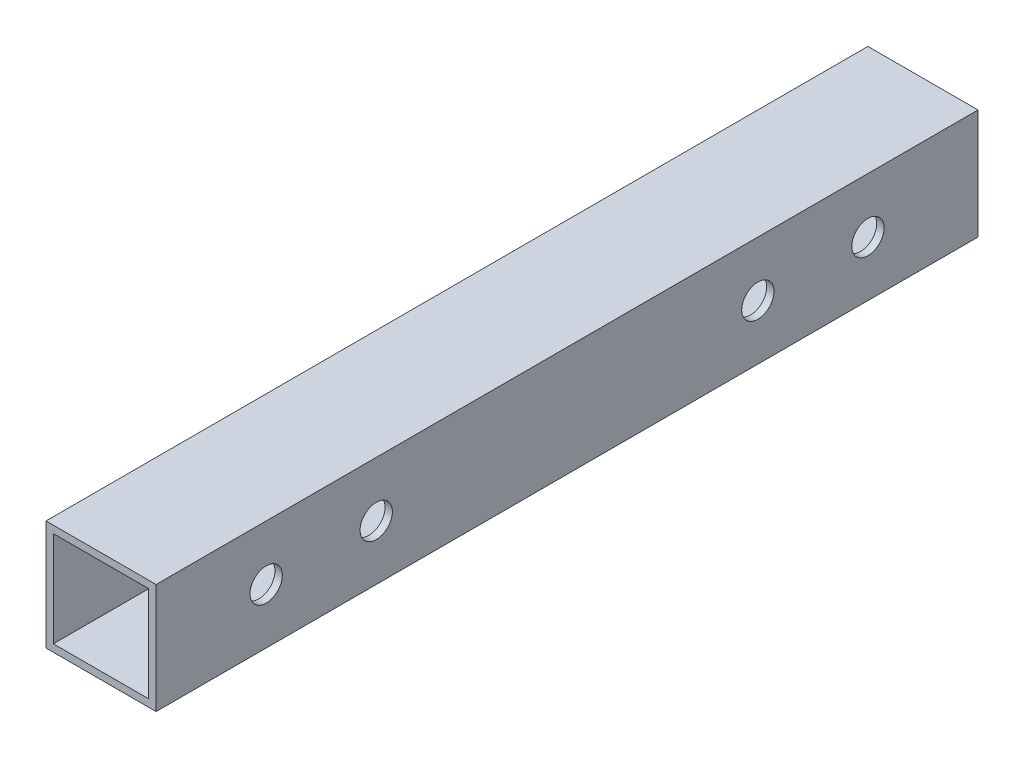
SolidWorks part; units mm, degrees
ref_plane "前视基准面" through (0, 0, 0) normal (0, 0, 1) x (1, 0, 0)
ref_plane "上视基准面" through (0, 0, 0) normal (0, 1, 0) x (1, 0, 0)
ref_plane "右视基准面" through (0, 0, 0) normal (1, 0, 0) x (0, 0, -1)
other "Configuration Table"
sketch "草图1" plane through (0, 0, 0) normal (0, 0, 1) x (1, 0, 0)
  line L1 (-7.5, 7.5) -> (7.5, 7.5)
  line L2 (-7.5, 7.5) -> (-7.5, -7.5)
  line L3 (-7.5, -7.5) -> (7.5, -7.5)
  line L4 (7.5, 7.5) -> (7.5, -7.5)
  line L5 (-7.5, 7.5) -> (7.5, -7.5) construction
  line L6 (-7.5, -7.5) -> (7.5, 7.5) construction
  line L7 (-6.5, 6.5) -> (6.5, 6.5)
  line L8 (-6.5, 6.5) -> (-6.5, -6.5)
  line L9 (-6.5, -6.5) -> (6.5, -6.5)
  line L10 (6.5, 6.5) -> (6.5, -6.5)
  line L11 (-6.5, 6.5) -> (6.5, -6.5) construction
  line L12 (-6.5, -6.5) -> (6.5, 6.5) construction
  point P0 (0, 0)
  point P5 (0, 0)
  dimension "D1" = 15
  dimension "D2" = 15
  dimension "D3" = 1
extrude "凸台-拉伸1" add sketch "草图1" along normal blind 112
sketch "草图3" plane through (7.5, 0, 0) normal (1, 0, 0) x (0, 0, -1)
  line L0 (-112, 0) -> (0, 0) construction
  line L1 (-112, -7.5) -> (-112, 7.5) construction
  line L2 (0, -7.5) -> (0, 7.5) construction
  line L3 (-56, 7.5) -> (-56, -7.5) construction
  line L4 (-112, 7.5) -> (0, 7.5) construction
  line L5 (-112, -7.5) -> (0, -7.5) construction
  circle A0 centre (-15, 0) radius 2.2
  circle A1 centre (-30, 0) radius 2.2
  circle A2 centre (-97, 0) radius 2.2
  circle A3 centre (-82, 0) radius 2.2
  dimension "D1" = 15
  dimension "D3" = 4.4
  dimension "D2" = 15
extrude "切除-拉伸1" cut sketch "草图3" against normal blind 55
